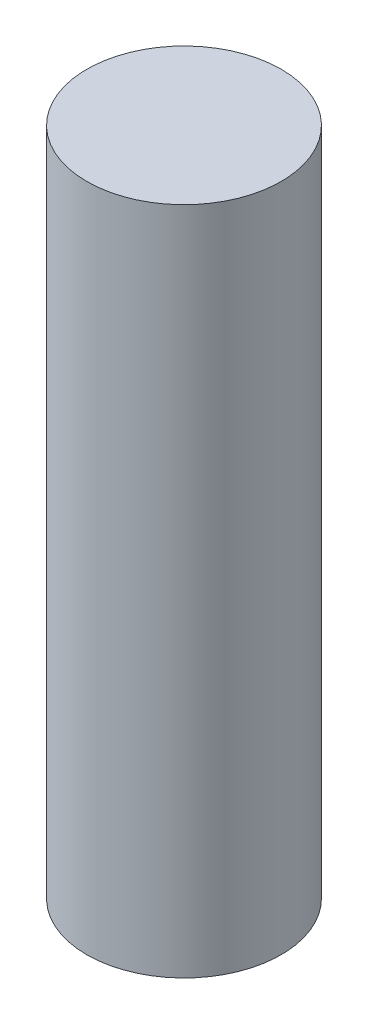
SolidWorks part; units mm, degrees
ref_plane "Front Plane" through (0, 0, 0) normal (0, 0, 1) x (1, 0, 0)
ref_plane "Top Plane" through (0, 0, 0) normal (0, 1, 0) x (1, 0, 0)
ref_plane "Right Plane" through (0, 0, 0) normal (1, 0, 0) x (0, 0, -1)
sketch "Sketch1" plane through (0, 0, 0) normal (0, 1, 0) x (1, 0, 0)
  circle A0 centre (0, 0) radius 3.683
  dimension "D1" = 7.366
extrude "Boss-Extrude1" add sketch "Sketch1" along normal blind 25.3721 contours A0
